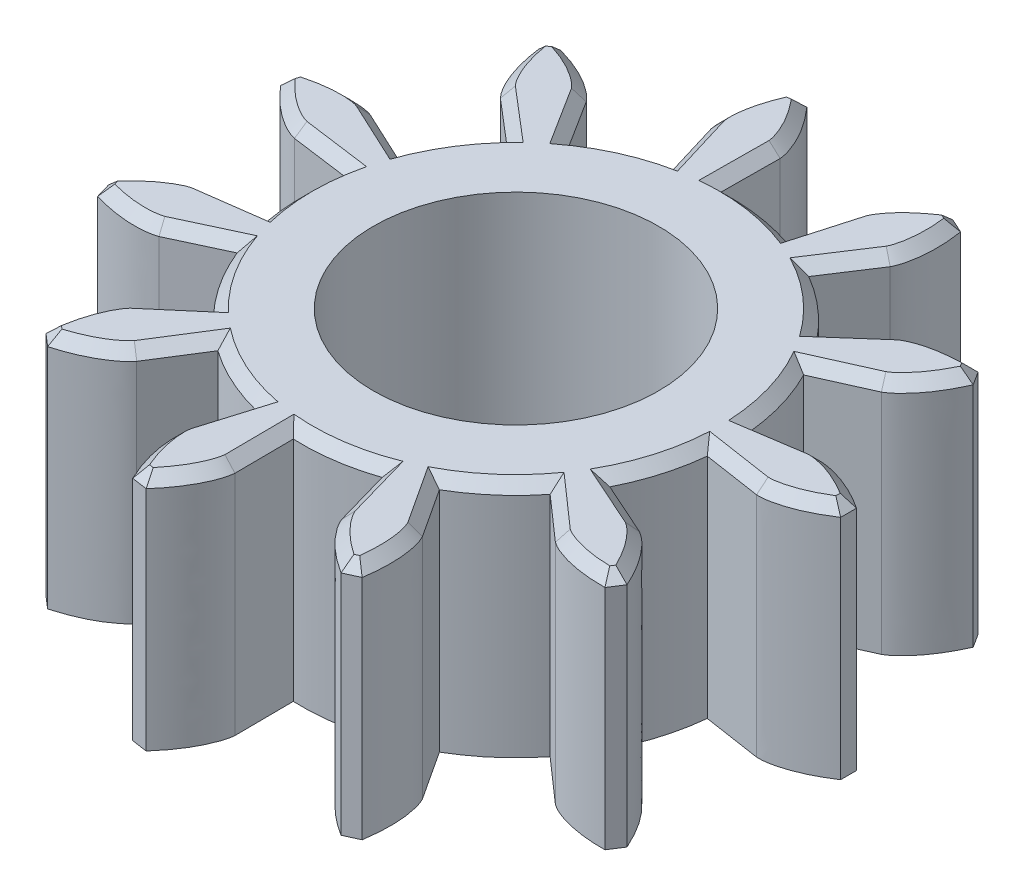
SolidWorks part; units mm, degrees
ref_plane "Front Plane" through (0, 0, 0) normal (0, 0, 1) x (1, 0, 0)
ref_plane "Top Plane" through (0, 0, 0) normal (0, 1, 0) x (1, 0, 0)
ref_plane "Right Plane" through (0, 0, 0) normal (1, 0, 0) x (0, 0, -1)
ref_plane "Plane1" through (0, -5, 0) normal (0, -1, 0) x (1, 0, 0)
sketch "Sketch1" plane through (0, -5, 0) normal (0, -1, 0) x (1, 0, 0)
  line L0 (3.1902, -2.808) -> (3.8796, -3.4147)
  line L1 (5.3253, -3.727) -> (5.6025, -3.2958)
  line L2 (4.7178, -2.1104) -> (3.8795, -1.7354)
  line L3 (4.2019, -0.6375) -> (5.1098, -0.7752)
  line L4 (6.4949, -0.2563) -> (6.4949, 0.2563)
  line L5 (5.1098, 0.7752) -> (4.2019, 0.6375)
  line L6 (3.8795, 1.7354) -> (4.7178, 2.1104)
  line L7 (5.6025, 3.2958) -> (5.3253, 3.727)
  line L8 (3.8796, 3.4147) -> (3.1902, 2.808)
  line L9 (2.3254, 3.5574) -> (2.8279, 4.326)
  line L10 (2.9312, 5.8015) -> (2.465, 6.0145)
  line L11 (1.4175, 4.9701) -> (1.1657, 4.087)
  line L12 (0.033, 4.2499) -> (0.0401, 5.1682)
  line L13 (-0.6706, 6.4653) -> (-1.178, 6.3924)
  line L14 (-1.4945, 4.9475) -> (-1.229, 4.0684)
  line L15 (-2.2699, 3.5931) -> (-2.7604, 4.3694)
  line L16 (-4.0596, 5.0764) -> (-4.447, 4.7407)
  line L17 (-3.9321, 3.3541) -> (-3.2334, 2.7581)
  line L18 (-3.8521, 1.7955) -> (-4.6844, 2.1834)
  line L19 (-6.1596, 2.0758) -> (-6.3041, 1.5839)
  line L20 (-5.1213, 0.6958) -> (-4.2113, 0.5722)
  line L21 (-4.2113, -0.5722) -> (-5.1213, -0.6958)
  line L22 (-6.3041, -1.5839) -> (-6.1596, -2.0758)
  line L23 (-4.6844, -2.1834) -> (-3.8521, -1.7955)
  line L24 (-3.2334, -2.7581) -> (-3.9321, -3.3541)
  line L25 (-4.447, -4.7407) -> (-4.0596, -5.0764)
  line L26 (-2.7604, -4.3694) -> (-2.2699, -3.5931)
  line L27 (-1.229, -4.0684) -> (-1.4945, -4.9475)
  line L28 (-1.178, -6.3924) -> (-0.6706, -6.4653)
  line L29 (0.0401, -5.1682) -> (0.033, -4.2499)
  line L30 (1.1657, -4.087) -> (1.4175, -4.9701)
  line L31 (2.465, -6.0145) -> (2.9312, -5.8015)
  line L32 (2.8279, -4.326) -> (2.3254, -3.5574)
  arc A0 (2.3254, -3.5574) -> (3.1902, -2.808) centre (0, 0) ccw
  arc A1 (3.8795, -1.7354) -> (4.2019, -0.6375) centre (0, 0) ccw
  arc A2 (4.2019, 0.6375) -> (3.8795, 1.7354) centre (0, 0) ccw
  arc A3 (3.1902, 2.808) -> (2.3254, 3.5574) centre (0, 0) ccw
  arc A4 (1.1657, 4.087) -> (0.033, 4.2499) centre (0, 0) ccw
  arc A5 (-1.229, 4.0684) -> (-2.2699, 3.5931) centre (0, 0) ccw
  arc A6 (-3.2334, 2.7581) -> (-3.8521, 1.7955) centre (0, 0) ccw
  arc A7 (-4.2113, 0.5722) -> (-4.2113, -0.5722) centre (0, 0) ccw
  arc A8 (-3.8521, -1.7955) -> (-3.2334, -2.7581) centre (0, 0) ccw
  arc A9 (-2.2699, -3.5931) -> (-1.229, -4.0684) centre (0, 0) ccw
  arc A10 (0.033, -4.2499) -> (1.1657, -4.087) centre (0, 0) ccw
  ellipse E0 centre (5.2837, -2.9889) end of major axis (6.9215, -2.923) minor radius 0.7393 (3.8796, -3.4147) -> (5.3253, -3.727) ccw
  ellipse E1 centre (4.9239, -3.5316) end of major axis (5.5451, -5.0133) minor radius 0.7173 (5.6025, -3.2958) -> (4.7178, -2.1104) ccw
  ellipse E2 centre (6.0609, 0.3422) end of major axis (7.403, 1.283) minor radius 0.7393 (5.1098, -0.7752) -> (6.4949, -0.2563) ccw
  ellipse E3 centre (6.0515, -0.3089) end of major axis (7.3752, -1.2195) minor radius 0.7173 (6.4949, 0.2563) -> (5.1098, 0.7752) ccw
  ellipse E4 centre (4.9137, 3.5646) end of major axis (4.2933, 2.0475) minor radius 0.7393 (4.7178, 2.1104) -> (5.6025, 3.2958) ccw
  ellipse E5 centre (5.2579, 3.0118) end of major axis (6.8637, 2.9614) minor radius 0.7173 (5.3253, 3.727) -> (3.8796, 3.4147) ccw
  ellipse E6 centre (2.2065, 5.6553) end of major axis (2.5048, 4.0436) minor radius 0.7393 (2.8279, 4.326) -> (2.9312, 5.8015) ccw
  ellipse E7 centre (2.7949, 5.3763) end of major axis (4.1731, 6.2021) minor radius 0.7173 (2.465, 6.0145) -> (1.4175, 4.9701) ccw
  ellipse E8 centre (-1.2013, 5.9505) end of major axis (-0.079, 4.7559) minor radius 0.7393 (0.0401, 5.1682) -> (-0.6706, 6.4653) ccw
  ellipse E9 centre (-0.5554, 6.0339) end of major axis (-1.2684, 4.5942) minor radius 0.7173 (-1.178, 6.3924) -> (-1.4945, 4.9475) ccw
  ellipse E10 centre (-4.2276, 4.3564) end of major axis (-2.6377, 3.9582) minor radius 0.7393 (-2.7604, 4.3694) -> (-4.0596, 5.0764) ccw
  ellipse E11 centre (-3.7295, 4.7758) end of major axis (-3.5509, 3.1791) minor radius 0.7173 (-4.447, 4.7407) -> (-3.9321, 3.3541) ccw
  ellipse E12 centre (-5.9118, 1.3792) end of major axis (-4.3589, 1.9038) minor radius 0.7393 (-4.6844, 2.1834) -> (-6.1596, 2.0758) ccw
  ellipse E13 centre (-5.7194, 2.0013) end of major axis (-4.7059, 0.7547) minor radius 0.7173 (-6.3041, 1.5839) -> (-5.1213, 0.6958) ccw
  ellipse E14 centre (-5.7189, -2.0359) end of major axis (-6.7417, -3.3167) minor radius 0.7393 (-5.1213, -0.6958) -> (-6.3041, -1.5839) ccw
  ellipse E15 centre (-5.8934, -1.4085) end of major axis (-4.3669, -1.9093) minor radius 0.7173 (-6.1596, -2.0758) -> (-4.6844, -2.1834) ccw
  ellipse E16 centre (-3.7104, -4.8046) end of major axis (-3.8783, -6.435) minor radius 0.7393 (-3.9321, -3.3541) -> (-4.447, -4.7407) ccw
  ellipse E17 centre (-4.1964, -4.3712) end of major axis (-2.6414, -3.9671) minor radius 0.7173 (-4.0596, -5.0764) -> (-2.7604, -4.3694) ccw
  ellipse E18 centre (-0.5238, -6.0479) end of major axis (0.2164, -7.5103) minor radius 0.7393 (-1.4945, -4.9475) -> (-1.178, -6.3924) ccw
  ellipse E19 centre (-1.167, -5.946) end of major axis (-2.2567, -7.1265) minor radius 0.7173 (-0.6706, -6.4653) -> (0.0401, -5.1682) ccw
  ellipse E20 centre (2.829, -5.371) end of major axis (4.2424, -6.2011) minor radius 0.7393 (1.4175, -4.9701) -> (2.465, -6.0145) ccw
  ellipse E21 centre (2.2329, -5.633) end of major axis (1.9544, -7.2153) minor radius 0.7173 (2.9312, -5.8015) -> (2.8279, -4.326) ccw
  point P4 (5.2837, -2.9889)
  point P5 (6.9215, -2.923)
  point P6 (5.3134, -3.7275)
  point P7 (3.8796, -3.4147)
  point P8 (5.3253, -3.727)
  point P9 (4.5558, -3.6748)
  point P10 (6.0117, -2.3029)
  point P18 (4.9239, -3.5316)
  point P19 (5.5853, -3.2543)
  point P20 (5.5451, -5.0133)
  point P21 (5.6025, -3.2958)
  point P22 (4.7178, -2.1104)
  point P23 (5.2353, -2.6175)
  point P24 (4.6124, -4.4457)
  point P34 (6.0609, 0.3422)
  point P35 (7.403, 1.283)
  point P36 (6.4852, -0.2632)
  point P37 (5.1098, -0.7752)
  point P38 (6.4949, -0.2563)
  point P39 (5.8193, -0.6284)
  point P40 (6.3024, 1.3128)
  point P48 (6.0515, -0.3089)
  point P49 (7.3752, -1.2195)
  point P50 (5.645, -0.8998)
  point P51 (6.4949, 0.2563)
  point P52 (5.1098, 0.7752)
  point P53 (5.8193, 0.6284)
  point P54 (6.2837, -1.2463)
  point P64 (4.9137, 3.5646)
  point P65 (5.598, 3.2848)
  point P66 (4.2933, 2.0475)
  point P67 (4.7178, 2.1104)
  point P68 (5.6025, 3.2958)
  point P69 (5.2353, 2.6175)
  point P70 (4.5921, 4.5117)
  point P78 (5.2579, 3.0118)
  point P79 (6.8637, 2.9614)
  point P80 (5.2354, 2.2949)
  point P81 (5.3253, 3.727)
  point P82 (3.8796, 3.4147)
  point P83 (4.5558, 3.6748)
  point P84 (5.96, 2.3488)
  point P94 (2.2065, 5.6553)
  point P95 (2.9334, 5.7898)
  point P96 (2.5048, 4.0436)
  point P97 (2.8279, 4.326)
  point P98 (2.9312, 5.8015)
  point P99 (2.9891, 5.0324)
  point P100 (1.4239, 6.2782)
  point P108 (2.7949, 5.3763)
  point P109 (4.1731, 6.2021)
  point P110 (3.1635, 4.7611)
  point P111 (2.465, 6.0145)
  point P112 (1.4175, 4.9701)
  point P113 (1.8458, 5.5545)
  point P114 (3.744, 5.1982)
  point P124 (-1.2013, 5.9505)
  point P125 (-0.6625, 6.4566)
  point P126 (-0.079, 4.7559)
  point P127 (0.0401, 5.1682)
  point P128 (-0.6706, 6.4653)
  point P129 (-0.2061, 5.8496)
  point P130 (-2.1964, 6.0514)
  point P138 (-0.5554, 6.0339)
  point P139 (0.0873, 5.7156)
  point P140 (-1.2684, 4.5942)
  point P141 (-1.178, 6.3924)
  point P142 (-1.4945, 4.9475)
  point P143 (-1.4502, 5.6707)
  point P144 (0.3393, 6.3971)
  point P154 (-4.2276, 4.3564)
  point P155 (-2.6377, 3.9582)
  point P156 (-4.4072, 3.6393)
  point P157 (-2.7604, 4.3694)
  point P158 (-4.0596, 5.0764)
  point P159 (-3.3359, 4.8095)
  point P160 (-5.1193, 3.9033)
  point P168 (-3.7295, 4.7758)
  point P169 (-3.0166, 4.8555)
  point P170 (-3.5509, 3.1791)
  point P171 (-4.447, 4.7407)
  point P172 (-3.9321, 3.3541)
  point P173 (-4.2858, 3.9864)
  point P174 (-3.1731, 5.5651)
  point P184 (-5.9118, 1.3792)
  point P185 (-4.3589, 1.9038)
  point P186 (-5.6752, 0.6788)
  point P187 (-4.6844, 2.1834)
  point P188 (-6.1596, 2.0758)
  point P189 (-5.4066, 2.2425)
  point P190 (-6.4169, 0.5159)
  point P198 (-5.7194, 2.0013)
  point P199 (-5.1628, 2.4538)
  point P200 (-4.7059, 0.7547)
  point P201 (-6.3041, 1.5839)
  point P202 (-5.1213, 0.6958)
  point P203 (-5.7607, 1.0365)
  point P204 (-5.6781, 2.9661)
  point P214 (-5.7189, -2.0359)
  point P215 (-5.1413, -2.4972)
  point P216 (-6.7417, -3.3167)
  point P217 (-5.1213, -0.6958)
  point P218 (-6.3041, -1.5839)
  point P219 (-5.7607, -1.0365)
  point P220 (-5.6772, -3.0352)
  point P228 (-5.8934, -1.4085)
  point P229 (-4.3669, -1.9093)
  point P230 (-6.117, -2.09)
  point P231 (-6.1596, -2.0758)
  point P232 (-4.6844, -2.1834)
  point P233 (-5.4066, -2.2425)
  point P234 (-6.3803, -0.5745)
  point P244 (-3.7104, -4.8046)
  point P245 (-2.975, -4.8803)
  point P246 (-3.8783, -6.435)
  point P247 (-3.9321, -3.3541)
  point P248 (-4.447, -4.7407)
  point P249 (-4.2858, -3.9864)
  point P250 (-3.135, -5.6227)
  point P258 (-4.1964, -4.3712)
  point P259 (-2.6414, -3.9671)
  point P260 (-4.016, -5.0654)
  point P261 (-4.0596, -5.0764)
  point P262 (-2.7604, -4.3694)
  point P263 (-3.3359, -4.8095)
  point P264 (-5.0568, -3.9328)
  point P274 (-0.5238, -6.0479)
  point P275 (0.1357, -5.714)
  point P276 (0.2164, -7.5103)
  point P277 (-1.4945, -4.9475)
  point P278 (-1.178, -6.3924)
  point P279 (-1.4502, -5.6707)
  point P280 (0.4025, -6.4251)
  point P288 (-1.167, -5.946)
  point P289 (-0.6399, -6.4325)
  point P290 (-2.2567, -7.1265)
  point P291 (-0.6706, -6.4653)
  point P292 (0.0401, -5.1682)
  point P293 (-0.2061, -5.8496)
  point P294 (-2.1279, -6.0424)
  point P304 (2.829, -5.371)
  point P305 (4.2424, -6.2011)
  point P306 (2.4547, -6.0085)
  point P307 (1.4175, -4.9701)
  point P308 (2.465, -6.0145)
  point P309 (1.8458, -5.5545)
  point P310 (3.8123, -5.1875)
  point P318 (2.2329, -5.633)
  point P319 (2.9393, -5.7573)
  point P320 (1.9544, -7.2153)
  point P321 (2.9312, -5.8015)
  point P322 (2.8279, -4.326)
  point P323 (2.9891, -5.0324)
  point P324 (1.4767, -6.2336)
extrude "Boss-Extrude1" add sketch "Sketch1" against normal blind 4.5
sketch "Sketch2" plane through (0, -0.5, 0) normal (0, 1, 0) x (1, 0, 0)
  line L0 (-0.1686, 4.0465) -> (-0.1599, 5.1595)
  line L1 (-0.7466, 6.2523) -> (-1.0451, 6.2094)
  line L2 (-1.3001, 4.9954) -> (-0.9783, 3.9301)
  line L3 (-2.3295, 3.313) -> (-2.924, 4.2539)
  line L4 (-4.0083, 4.8562) -> (-4.2363, 4.6587)
  line L5 (-3.7944, 3.4995) -> (-2.9477, 2.7773)
  line L6 (-3.7508, 1.5276) -> (-4.7597, 1.9978)
  line L7 (-5.9975, 1.9182) -> (-6.0824, 1.6288)
  line L8 (-5.084, 0.8926) -> (-3.9813, 0.7427)
  line L9 (-3.9813, -0.7427) -> (-5.0842, -0.8926)
  line L10 (-6.0825, -1.6288) -> (-5.9975, -1.9182)
  line L11 (-4.7595, -1.9978) -> (-3.7508, -1.5276)
  line L12 (-2.9477, -2.7773) -> (-3.7945, -3.4996)
  line L13 (-4.2363, -4.6586) -> (-4.0083, -4.8562)
  line L14 (-2.9239, -4.2538) -> (-2.3295, -3.313)
  line L15 (-0.9783, -3.9301) -> (-1.3001, -4.9955)
  line L16 (-1.0452, -6.2094) -> (-0.7466, -6.2523)
  line L17 (-0.1599, -5.1593) -> (-0.1686, -4.0465)
  line L18 (1.3018, -3.8351) -> (1.6071, -4.9054)
  line L19 (2.4778, -5.7887) -> (2.7522, -5.6634)
  line L20 (2.6548, -4.4268) -> (2.0459, -3.4953)
  line L21 (3.1685, -2.5225) -> (4.004, -3.2579)
  line L22 (5.2141, -3.5302) -> (5.3772, -3.2764)
  line L23 (4.6266, -2.2888) -> (3.6108, -1.8343)
  line L24 (4.0293, -0.409) -> (5.1297, -0.576)
  line L25 (6.2949, -0.1508) -> (6.2949, 0.1508)
  line L26 (5.1296, 0.5759) -> (4.0293, 0.409)
  line L27 (3.6108, 1.8343) -> (4.6268, 2.2888)
  line L28 (5.3772, 3.2764) -> (5.2141, 3.5302)
  line L29 (4.0039, 3.2578) -> (3.1685, 2.5225)
  line L30 (2.0459, 3.4953) -> (2.6549, 4.4269)
  line L31 (2.7522, 5.6634) -> (2.4778, 5.7887)
  line L32 (1.607, 4.9053) -> (1.3018, 3.8351)
  line L33 (2.3254, 3.5574) -> (2.8279, 4.326)
  line L34 (2.9312, 5.8015) -> (2.465, 6.0145)
  line L35 (1.4175, 4.9701) -> (1.1657, 4.087)
  line L36 (0.033, 4.2499) -> (0.0401, 5.1682)
  line L37 (-0.6706, 6.4653) -> (-1.178, 6.3924)
  line L38 (-1.4945, 4.9475) -> (-1.229, 4.0684)
  line L39 (-2.2699, 3.5931) -> (-2.7604, 4.3694)
  line L40 (-4.0596, 5.0764) -> (-4.447, 4.7407)
  line L41 (-3.9321, 3.3541) -> (-3.2334, 2.7581)
  line L42 (-3.8521, 1.7955) -> (-4.6844, 2.1834)
  line L43 (-6.1596, 2.0758) -> (-6.3041, 1.5839)
  line L44 (-5.1213, 0.6958) -> (-4.2113, 0.5722)
  line L45 (-4.2113, -0.5722) -> (-5.1213, -0.6958)
  line L46 (-6.3041, -1.5839) -> (-6.1596, -2.0758)
  line L47 (-4.6844, -2.1834) -> (-3.8521, -1.7955)
  line L48 (-3.2334, -2.7581) -> (-3.9321, -3.3541)
  line L49 (-4.447, -4.7407) -> (-4.0596, -5.0764)
  line L50 (-2.7604, -4.3694) -> (-2.2699, -3.5931)
  line L51 (-1.229, -4.0684) -> (-1.4945, -4.9475)
  line L52 (-1.178, -6.3924) -> (-0.6706, -6.4653)
  line L53 (0.0401, -5.1682) -> (0.033, -4.2499)
  line L54 (1.1657, -4.087) -> (1.4175, -4.9701)
  line L55 (2.465, -6.0145) -> (2.9312, -5.8015)
  line L56 (2.8279, -4.326) -> (2.3254, -3.5574)
  line L57 (3.1902, -2.808) -> (3.8796, -3.4147)
  line L58 (5.3253, -3.727) -> (5.6025, -3.2958)
  line L59 (4.7178, -2.1104) -> (3.8795, -1.7354)
  line L60 (4.2019, -0.6375) -> (5.1098, -0.7752)
  line L61 (6.4949, -0.2563) -> (6.4949, 0.2563)
  line L62 (5.1098, 0.7752) -> (4.2019, 0.6375)
  line L63 (3.8795, 1.7354) -> (4.7178, 2.1104)
  line L64 (5.6025, 3.2958) -> (5.3253, 3.727)
  line L65 (3.8796, 3.4147) -> (3.1902, 2.808)
  line L66 (2.3254, 3.5574) -> (2.8279, 4.326)
  line L67 (2.9312, 5.8015) -> (2.465, 6.0145)
  line L68 (1.4175, 4.9701) -> (1.1657, 4.087)
  line L69 (0.033, 4.2499) -> (0.0401, 5.1682)
  line L70 (-0.6706, 6.4653) -> (-1.178, 6.3924)
  line L71 (-1.4945, 4.9475) -> (-1.229, 4.0684)
  line L72 (-2.2699, 3.5931) -> (-2.7604, 4.3694)
  line L73 (-4.0596, 5.0764) -> (-4.447, 4.7407)
  line L74 (-3.9321, 3.3541) -> (-3.2334, 2.7581)
  line L75 (-3.8521, 1.7955) -> (-4.6844, 2.1834)
  line L76 (-6.1596, 2.0758) -> (-6.3041, 1.5839)
  line L77 (-5.1213, 0.6958) -> (-4.2113, 0.5722)
  line L78 (-4.2113, -0.5722) -> (-5.1213, -0.6958)
  line L79 (-6.3041, -1.5839) -> (-6.1596, -2.0758)
  line L80 (-4.6844, -2.1834) -> (-3.8521, -1.7955)
  line L81 (-3.2334, -2.7581) -> (-3.9321, -3.3541)
  line L82 (-4.447, -4.7407) -> (-4.0596, -5.0764)
  line L83 (-2.7604, -4.3694) -> (-2.2699, -3.5931)
  line L84 (-1.229, -4.0684) -> (-1.4945, -4.9475)
  line L85 (-1.178, -6.3924) -> (-0.6706, -6.4653)
  line L86 (0.0401, -5.1682) -> (0.033, -4.2499)
  line L87 (1.1657, -4.087) -> (1.4175, -4.9701)
  line L88 (2.465, -6.0145) -> (2.9312, -5.8015)
  line L89 (2.8279, -4.326) -> (2.3254, -3.5574)
  line L90 (3.1902, -2.808) -> (3.8796, -3.4147)
  line L91 (5.3253, -3.727) -> (5.6025, -3.2958)
  line L92 (4.7178, -2.1104) -> (3.8795, -1.7354)
  line L93 (4.2019, -0.6375) -> (5.1098, -0.7752)
  line L94 (6.4949, -0.2563) -> (6.4949, 0.2563)
  line L95 (5.1098, 0.7752) -> (4.2019, 0.6375)
  line L96 (3.8795, 1.7354) -> (4.7178, 2.1104)
  line L97 (5.6025, 3.2958) -> (5.3253, 3.727)
  line L98 (3.8796, 3.4147) -> (3.1902, 2.808)
  arc A0 (-0.9783, 3.9301) -> (-2.3295, 3.313) centre (0, 0) ccw
  arc A1 (-2.9477, 2.7773) -> (-3.7508, 1.5276) centre (0, 0) ccw
  arc A2 (-3.9813, 0.7427) -> (-3.9813, -0.7427) centre (0, 0) ccw
  arc A3 (-3.7508, -1.5276) -> (-2.9477, -2.7773) centre (0, 0) ccw
  arc A4 (-2.3295, -3.313) -> (-0.9783, -3.9301) centre (0, 0) ccw
  arc A5 (-0.1686, -4.0465) -> (1.3018, -3.8351) centre (0, 0) ccw
  arc A6 (2.0459, -3.4953) -> (3.1685, -2.5225) centre (0, 0) ccw
  arc A7 (3.6108, -1.8343) -> (4.0293, -0.409) centre (0, 0) ccw
  arc A8 (4.0293, 0.409) -> (3.6108, 1.8343) centre (0, 0) ccw
  arc A9 (3.1685, 2.5225) -> (2.0459, 3.4953) centre (0, 0) ccw
  arc A10 (1.3018, 3.8351) -> (-0.1686, 4.0465) centre (0, 0) ccw
  arc A11 (3.1902, 2.808) -> (2.3254, 3.5574) centre (0, 0) ccw
  arc A12 (1.1657, 4.087) -> (0.033, 4.2499) centre (0, 0) ccw
  arc A13 (-1.229, 4.0684) -> (-2.2699, 3.5931) centre (0, 0) ccw
  arc A14 (-3.2334, 2.7581) -> (-3.8521, 1.7955) centre (0, 0) ccw
  arc A15 (-4.2113, 0.5722) -> (-4.2113, -0.5722) centre (0, 0) ccw
  arc A16 (-3.8521, -1.7955) -> (-3.2334, -2.7581) centre (0, 0) ccw
  arc A17 (-2.2699, -3.5931) -> (-1.229, -4.0684) centre (0, 0) ccw
  arc A18 (0.033, -4.2499) -> (1.1657, -4.087) centre (0, 0) ccw
  arc A19 (2.3254, -3.5574) -> (3.1902, -2.808) centre (0, 0) ccw
  arc A20 (3.8795, -1.7354) -> (4.2019, -0.6375) centre (0, 0) ccw
  arc A21 (4.2019, 0.6375) -> (3.8795, 1.7354) centre (0, 0) ccw
  arc A22 (3.1902, 2.808) -> (2.3254, 3.5574) centre (0, 0) ccw
  arc A23 (1.1657, 4.087) -> (0.033, 4.2499) centre (0, 0) ccw
  arc A24 (-1.229, 4.0684) -> (-2.2699, 3.5931) centre (0, 0) ccw
  arc A25 (-3.2334, 2.7581) -> (-3.8521, 1.7955) centre (0, 0) ccw
  arc A26 (-4.2113, 0.5722) -> (-4.2113, -0.5722) centre (0, 0) ccw
  arc A27 (-3.8521, -1.7955) -> (-3.2334, -2.7581) centre (0, 0) ccw
  arc A28 (-2.2699, -3.5931) -> (-1.229, -4.0684) centre (0, 0) ccw
  arc A29 (0.033, -4.2499) -> (1.1657, -4.087) centre (0, 0) ccw
  arc A30 (2.3254, -3.5574) -> (3.1902, -2.808) centre (0, 0) ccw
  arc A31 (3.8795, -1.7354) -> (4.2019, -0.6375) centre (0, 0) ccw
  arc A32 (4.2019, 0.6375) -> (3.8795, 1.7354) centre (0, 0) ccw
  circle A33 centre (0, 0) radius 2.7
  ellipse E22 centre (2.2329, 5.633) end of major axis (1.9544, 7.2153) minor radius 0.7173 (2.8279, 4.326) -> (2.9312, 5.8015) ccw
  ellipse E23 centre (2.829, 5.371) end of major axis (4.2424, 6.2011) minor radius 0.7393 (2.465, 6.0145) -> (1.4175, 4.9701) ccw
  ellipse E24 centre (-1.167, 5.946) end of major axis (-2.2567, 7.1265) minor radius 0.7173 (0.0401, 5.1682) -> (-0.6706, 6.4653) ccw
  ellipse E25 centre (-0.5238, 6.0479) end of major axis (0.2164, 7.5103) minor radius 0.7393 (-1.178, 6.3924) -> (-1.4945, 4.9475) ccw
  ellipse E26 centre (-4.1964, 4.3712) end of major axis (-2.6414, 3.9671) minor radius 0.7173 (-2.7604, 4.3694) -> (-4.0596, 5.0764) ccw
  ellipse E27 centre (-3.7104, 4.8046) end of major axis (-3.8783, 6.435) minor radius 0.7393 (-4.447, 4.7407) -> (-3.9321, 3.3541) ccw
  ellipse E28 centre (-5.8934, 1.4085) end of major axis (-4.3669, 1.9093) minor radius 0.7173 (-4.6844, 2.1834) -> (-6.1596, 2.0758) ccw
  ellipse E29 centre (-5.7189, 2.0359) end of major axis (-6.7417, 3.3167) minor radius 0.7393 (-6.3041, 1.5839) -> (-5.1213, 0.6958) ccw
  ellipse E30 centre (-5.7194, -2.0013) end of major axis (-4.7059, -0.7547) minor radius 0.7173 (-5.1213, -0.6958) -> (-6.3041, -1.5839) ccw
  ellipse E31 centre (-5.9118, -1.3792) end of major axis (-4.3589, -1.9038) minor radius 0.7393 (-6.1596, -2.0758) -> (-4.6844, -2.1834) ccw
  ellipse E32 centre (-3.7295, -4.7758) end of major axis (-3.5509, -3.1791) minor radius 0.7173 (-3.9321, -3.3541) -> (-4.447, -4.7407) ccw
  ellipse E33 centre (-4.2276, -4.3564) end of major axis (-2.6377, -3.9582) minor radius 0.7393 (-4.0596, -5.0764) -> (-2.7604, -4.3694) ccw
  ellipse E34 centre (-0.5554, -6.0339) end of major axis (-1.2684, -4.5942) minor radius 0.7173 (-1.4945, -4.9475) -> (-1.178, -6.3924) ccw
  ellipse E35 centre (-1.2013, -5.9505) end of major axis (-0.079, -4.7559) minor radius 0.7393 (-0.6706, -6.4653) -> (0.0401, -5.1682) ccw
  ellipse E36 centre (2.7949, -5.3763) end of major axis (4.1731, -6.2021) minor radius 0.7173 (1.4175, -4.9701) -> (2.465, -6.0145) ccw
  ellipse E37 centre (2.2065, -5.6553) end of major axis (2.5048, -4.0436) minor radius 0.7393 (2.9312, -5.8015) -> (2.8279, -4.326) ccw
  ellipse E38 centre (5.2579, -3.0118) end of major axis (3.6521, -3.0623) minor radius 0.7173 (3.8796, -3.4147) -> (5.3253, -3.727) ccw
  ellipse E39 centre (4.9137, -3.5646) end of major axis (4.2933, -2.0475) minor radius 0.7393 (5.6025, -3.2958) -> (4.7178, -2.1104) ccw
  ellipse E40 centre (6.0515, 0.3089) end of major axis (4.7279, -0.6017) minor radius 0.7173 (5.1098, -0.7752) -> (6.4949, -0.2563) ccw
  ellipse E41 centre (6.0609, -0.3422) end of major axis (7.403, -1.283) minor radius 0.7393 (6.4949, 0.2563) -> (5.1098, 0.7752) ccw
  ellipse E42 centre (4.9239, 3.5316) end of major axis (5.5451, 5.0133) minor radius 0.7173 (4.7178, 2.1104) -> (5.6025, 3.2958) ccw
  ellipse E43 centre (5.2837, 2.9889) end of major axis (3.646, 3.0547) minor radius 0.7393 (5.3253, 3.727) -> (3.8796, 3.4147) ccw
  ellipse E44 centre (2.2329, 5.633) end of major axis (1.9544, 7.2153) minor radius 0.7173 (2.8279, 4.326) -> (2.9312, 5.8015) ccw
  ellipse E45 centre (2.829, 5.371) end of major axis (4.2424, 6.2011) minor radius 0.7393 (2.465, 6.0145) -> (1.4175, 4.9701) ccw
  ellipse E46 centre (-1.167, 5.946) end of major axis (-2.2567, 7.1265) minor radius 0.7173 (0.0401, 5.1682) -> (-0.6706, 6.4653) ccw
  ellipse E47 centre (-0.5238, 6.0479) end of major axis (0.2164, 7.5103) minor radius 0.7393 (-1.178, 6.3924) -> (-1.4945, 4.9475) ccw
  ellipse E48 centre (-4.1964, 4.3712) end of major axis (-2.6414, 3.9671) minor radius 0.7173 (-2.7604, 4.3694) -> (-4.0596, 5.0764) ccw
  ellipse E49 centre (-3.7104, 4.8046) end of major axis (-3.8783, 6.435) minor radius 0.7393 (-4.447, 4.7407) -> (-3.9321, 3.3541) ccw
  ellipse E50 centre (-5.8934, 1.4085) end of major axis (-4.3669, 1.9093) minor radius 0.7173 (-4.6844, 2.1834) -> (-6.1596, 2.0758) ccw
  ellipse E51 centre (-5.7189, 2.0359) end of major axis (-6.7417, 3.3167) minor radius 0.7393 (-6.3041, 1.5839) -> (-5.1213, 0.6958) ccw
  ellipse E52 centre (-5.7194, -2.0013) end of major axis (-4.7059, -0.7547) minor radius 0.7173 (-5.1213, -0.6958) -> (-6.3041, -1.5839) ccw
  ellipse E53 centre (-5.9118, -1.3792) end of major axis (-4.3589, -1.9038) minor radius 0.7393 (-6.1596, -2.0758) -> (-4.6844, -2.1834) ccw
  ellipse E54 centre (-3.7295, -4.7758) end of major axis (-3.5509, -3.1791) minor radius 0.7173 (-3.9321, -3.3541) -> (-4.447, -4.7407) ccw
  ellipse E55 centre (-4.2276, -4.3564) end of major axis (-2.6377, -3.9582) minor radius 0.7393 (-4.0596, -5.0764) -> (-2.7604, -4.3694) ccw
  ellipse E56 centre (-0.5554, -6.0339) end of major axis (-1.2684, -4.5942) minor radius 0.7173 (-1.4945, -4.9475) -> (-1.178, -6.3924) ccw
  ellipse E57 centre (-1.2013, -5.9505) end of major axis (-0.079, -4.7559) minor radius 0.7393 (-0.6706, -6.4653) -> (0.0401, -5.1682) ccw
  ellipse E58 centre (2.7949, -5.3763) end of major axis (4.1731, -6.2021) minor radius 0.7173 (1.4175, -4.9701) -> (2.465, -6.0145) ccw
  ellipse E59 centre (2.2065, -5.6553) end of major axis (2.5048, -4.0436) minor radius 0.7393 (2.9312, -5.8015) -> (2.8279, -4.326) ccw
  ellipse E60 centre (5.2579, -3.0118) end of major axis (6.8637, -2.9614) minor radius 0.7173 (3.8796, -3.4147) -> (5.3253, -3.727) ccw
  ellipse E61 centre (4.9137, -3.5646) end of major axis (4.2933, -2.0475) minor radius 0.7393 (5.6025, -3.2958) -> (4.7178, -2.1104) ccw
  ellipse E62 centre (6.0515, 0.3089) end of major axis (7.3752, 1.2195) minor radius 0.7173 (5.1098, -0.7752) -> (6.4949, -0.2563) ccw
  ellipse E63 centre (6.0609, -0.3422) end of major axis (7.403, -1.283) minor radius 0.7393 (6.4949, 0.2563) -> (5.1098, 0.7752) ccw
  ellipse E64 centre (4.9239, 3.5316) end of major axis (5.5451, 5.0133) minor radius 0.7173 (4.7178, 2.1104) -> (5.6025, 3.2958) ccw
  ellipse E65 centre (5.2837, 2.9889) end of major axis (6.9215, 2.923) minor radius 0.7393 (5.3253, 3.727) -> (3.8796, 3.4147) ccw
  spline S0 degree 1 poles (-0.1599, 5.1595) (-0.7466, 6.2523) knots 0 0 1 1 construction
  spline S1 degree 1 poles (-1.0451, 6.2094) (-1.3001, 4.9954) knots 0 0 1 1 construction
  spline S2 degree 1 poles (-2.924, 4.2539) (-4.0083, 4.8562) knots 0 0 1 1 construction
  spline S3 degree 1 poles (-4.2363, 4.6587) (-3.7944, 3.4995) knots 0 0 1 1 construction
  spline S4 degree 1 poles (-4.7597, 1.9978) (-5.9975, 1.9182) knots 0 0 1 1 construction
  spline S5 degree 1 poles (-6.0824, 1.6288) (-5.084, 0.8926) knots 0 0 1 1 construction
  spline S6 degree 1 poles (-5.0842, -0.8926) (-6.0825, -1.6288) knots 0 0 1 1 construction
  spline S7 degree 1 poles (-5.9975, -1.9182) (-4.7595, -1.9978) knots 0 0 1 1 construction
  spline S8 degree 1 poles (-3.7945, -3.4996) (-4.2363, -4.6586) knots 0 0 1 1 construction
  spline S9 degree 1 poles (-4.0083, -4.8562) (-2.9239, -4.2538) knots 0 0 1 1 construction
  spline S10 degree 1 poles (-1.3001, -4.9955) (-1.0452, -6.2094) knots 0 0 1 1 construction
  spline S11 degree 1 poles (-0.7466, -6.2523) (-0.1599, -5.1593) knots 0 0 1 1 construction
  spline S12 degree 1 poles (1.6071, -4.9054) (2.4778, -5.7887) knots 0 0 1 1 construction
  spline S13 degree 1 poles (2.7522, -5.6634) (2.6548, -4.4268) knots 0 0 1 1 construction
  spline S14 degree 1 poles (4.004, -3.2579) (5.2141, -3.5302) knots 0 0 1 1 construction
  spline S15 degree 1 poles (5.3772, -3.2764) (4.6266, -2.2888) knots 0 0 1 1 construction
  spline S16 degree 1 poles (5.1297, -0.576) (6.2949, -0.1508) knots 0 0 1 1 construction
  spline S17 degree 1 poles (6.2949, 0.1508) (5.1296, 0.5759) knots 0 0 1 1 construction
  spline S18 degree 1 poles (4.6268, 2.2888) (5.3772, 3.2764) knots 0 0 1 1 construction
  spline S19 degree 1 poles (5.2141, 3.5302) (4.0039, 3.2578) knots 0 0 1 1 construction
  spline S20 degree 1 poles (2.6549, 4.4269) (2.7522, 5.6634) knots 0 0 1 1 construction
  spline S21 degree 1 poles (2.4778, 5.7887) (1.607, 4.9053) knots 0 0 1 1 construction
  spline S22 degree 3 poles (-0.1599, 5.1595) (-0.1679, 5.2382) (-0.201, 5.3778) (-0.3234, 5.6652) (-0.5064, 5.9612) (-0.6642, 6.1599) (-0.7466, 6.2523) knots -2.605383 -2.605383 -2.605383 -2.605383 -2.356634 -2.107886 -1.859137 -1.610389 -1.610389 -1.610389 -1.610389
  spline S23 degree 3 poles (-1.0451, 6.2094) (-1.0981, 6.0974) (-1.1937, 5.862) (-1.2857, 5.5272) (-1.3222, 5.2176) (-1.3145, 5.0735) (-1.3001, 4.9954) knots 1.629777 1.629777 1.629777 1.629777 1.874231 2.118685 2.363139 2.607593 2.607593 2.607593 2.607593
  spline S24 degree 3 poles (-2.924, 4.2539) (-2.9732, 4.3158) (-3.0765, 4.4154) (-3.3349, 4.591) (-3.6488, 4.7411) (-3.889, 4.8229) (-4.0083, 4.8562) knots 0.53621 0.53621 0.53621 0.53621 0.784958 1.033707 1.282455 1.531204 1.531204 1.531204 1.531204
  spline S25 degree 3 poles (-4.2363, 4.6587) (-4.2203, 4.5358) (-4.1734, 4.286) (-4.0698, 3.9547) (-3.9331, 3.6745) (-3.8488, 3.5574) (-3.7944, 3.4995) knots 1.629777 1.629777 1.629777 1.629777 1.874231 2.118685 2.363139 2.607593 2.607593 2.607593 2.607593
  spline S26 degree 3 poles (-4.7597, 1.9978) (-4.8346, 2.0233) (-4.9753, 2.0512) (-5.2876, 2.0592) (-5.6328, 2.0157) (-5.8791, 1.9547) (-5.9975, 1.9182) knots 0.53621 0.53621 0.53621 0.53621 0.784958 1.033707 1.282455 1.531204 1.531204 1.531204 1.531204
  spline S27 degree 3 poles (-6.0824, 1.6288) (-6.0026, 1.5341) (-5.8281, 1.3493) (-5.5618, 1.1266) (-5.2953, 0.9647) (-5.1611, 0.9119) (-5.084, 0.8926) knots 1.629777 1.629777 1.629777 1.629777 1.874231 2.118685 2.363139 2.607593 2.607593 2.607593 2.607593
  spline S28 degree 3 poles (-5.0842, -0.8926) (-5.161, -0.9117) (-5.2945, -0.9643) (-5.5615, -1.1264) (-5.8284, -1.3496) (-6.0026, -1.5341) (-6.0825, -1.6288) knots 0.53621 0.53621 0.53621 0.53621 0.784958 1.033707 1.282455 1.531204 1.531204 1.531204 1.531204
  spline S29 degree 3 poles (-5.9975, -1.9182) (-5.8791, -1.9547) (-5.6324, -2.0158) (-5.288, -2.0592) (-4.9763, -2.0513) (-4.8347, -2.0232) (-4.7595, -1.9978) knots -1.511816 -1.511816 -1.511816 -1.511816 -1.267362 -1.022908 -0.778454 -0.534 -0.534 -0.534 -0.534
  spline S30 degree 3 poles (-3.7945, -3.4996) (-3.8488, -3.5572) (-3.9327, -3.6736) (-4.0697, -3.9543) (-4.1735, -4.2864) (-4.2204, -4.5358) (-4.2363, -4.6586) knots 0.53621 0.53621 0.53621 0.53621 0.784958 1.033707 1.282455 1.531204 1.531204 1.531204 1.531204
  spline S31 degree 3 poles (-4.0083, -4.8562) (-3.889, -4.8229) (-3.6485, -4.7409) (-3.3352, -4.5912) (-3.0773, -4.416) (-2.9734, -4.3159) (-2.9239, -4.2538) knots -1.511816 -1.511816 -1.511816 -1.511816 -1.267362 -1.022908 -0.778454 -0.534 -0.534 -0.534 -0.534
  spline S32 degree 3 poles (-1.3001, -4.9955) (-1.3146, -5.0733) (-1.3223, -5.2166) (-1.2858, -5.5268) (-1.1936, -5.8623) (-1.0982, -6.0975) (-1.0452, -6.2094) knots 0.53621 0.53621 0.53621 0.53621 0.784958 1.033707 1.282455 1.531204 1.531204 1.531204 1.531204
  spline S33 degree 3 poles (-0.7466, -6.2523) (-0.6642, -6.1598) (-0.5061, -5.9608) (-0.3236, -5.6655) (-0.2013, -5.3787) (-0.1681, -5.2383) (-0.1599, -5.1593) knots -1.511816 -1.511816 -1.511816 -1.511816 -1.267362 -1.022908 -0.778454 -0.534 -0.534 -0.534 -0.534
  spline S34 degree 3 poles (1.6071, -4.9054) (1.6369, -4.9787) (1.7079, -5.1033) (1.9064, -5.3446) (2.1653, -5.577) (2.3727, -5.7232) (2.4778, -5.7887) knots -2.605383 -2.605383 -2.605383 -2.605383 -2.356634 -2.107886 -1.859137 -1.610389 -1.610389 -1.610389 -1.610389
  spline S35 degree 3 poles (2.7522, -5.6634) (2.7715, -5.541) (2.7969, -5.2882) (2.7908, -4.9411) (2.7386, -4.6337) (2.6906, -4.4976) (2.6548, -4.4268) knots -1.511816 -1.511816 -1.511816 -1.511816 -1.267362 -1.022908 -0.778454 -0.534 -0.534 -0.534 -0.534
  spline S36 degree 3 poles (4.004, -3.2579) (4.0687, -3.3034) (4.1959, -3.3698) (4.4933, -3.4655) (4.8367, -3.521) (5.0903, -3.5319) (5.2141, -3.5302) knots -2.605383 -2.605383 -2.605383 -2.605383 -2.356634 -2.107886 -1.859137 -1.610389 -1.610389 -1.610389 -1.610389
  spline S37 degree 3 poles (5.3772, -3.2764) (5.3272, -3.163) (5.2119, -2.9366) (5.0191, -2.6479) (4.809, -2.4175) (4.6951, -2.329) (4.6266, -2.2888) knots -1.511816 -1.511816 -1.511816 -1.511816 -1.267362 -1.022908 -0.778454 -0.534 -0.534 -0.534 -0.534
  spline S38 degree 3 poles (5.1297, -0.576) (5.2088, -0.5792) (5.3517, -0.5664) (5.6536, -0.4861) (5.9725, -0.3471) (6.1917, -0.2192) (6.2949, -0.1508) knots -2.605383 -2.605383 -2.605383 -2.605383 -2.356634 -2.107886 -1.859137 -1.610389 -1.610389 -1.610389 -1.610389
  spline S39 degree 3 poles (6.2949, 0.1508) (6.1916, 0.2192) (5.9722, 0.3473) (5.6539, 0.486) (5.3526, 0.5662) (5.2089, 0.5791) (5.1296, 0.5759) knots 1.629777 1.629777 1.629777 1.629777 1.874231 2.118685 2.363139 2.607593 2.607593 2.607593 2.607593
  spline S40 degree 3 poles (4.6268, 2.2888) (4.6951, 2.3288) (4.8083, 2.4168) (5.0189, 2.6476) (5.2121, 2.937) (5.3273, 3.1631) (5.3772, 3.2764) knots -2.605383 -2.605383 -2.605383 -2.605383 -2.356634 -2.107886 -1.859137 -1.610389 -1.610389 -1.610389 -1.610389
  spline S41 degree 3 poles (5.2141, 3.5302) (5.0902, 3.5318) (4.8363, 3.521) (4.4936, 3.4656) (4.1968, 3.3702) (4.0689, 3.3033) (4.0039, 3.2578) knots 1.629777 1.629777 1.629777 1.629777 1.874231 2.118685 2.363139 2.607593 2.607593 2.607593 2.607593
  spline S42 degree 3 poles (2.6549, 4.4269) (2.6907, 4.4974) (2.7384, 4.6327) (2.7908, 4.9407) (2.7969, 5.2886) (2.7715, 5.5411) (2.7522, 5.6634) knots -2.605383 -2.605383 -2.605383 -2.605383 -2.356634 -2.107886 -1.859137 -1.610389 -1.610389 -1.610389 -1.610389
  spline S43 degree 3 poles (2.4778, 5.7887) (2.3727, 5.7231) (2.165, 5.5768) (1.9066, 5.3449) (1.7085, 5.1041) (1.6371, 4.9788) (1.607, 4.9053) knots 1.629777 1.629777 1.629777 1.629777 1.874231 2.118685 2.363139 2.607593 2.607593 2.607593 2.607593
  dimension "D3" = 5.4
  dimension "D1" = 0
  dimension "D2" = 0.2
extrude "Cut-Extrude1" cut sketch "Sketch2" against normal through all contours L97 E65 L98 A22 L66 E44 L67 E45 L68 A23 L69 E46 L70 E47 L71 A24 L72 E48 L73 E49 L74 A25 L75 E50 L76 E51 L77 A26 L78 E52 L79 E53 L80 A27 L81 E54 L82 E55 L83 A28 L84 E56 L85 E57 L86 A29 L87 E58 L88 E59 L89 | A33 | L31 S43 L32 A10 L0 S22 L1 S23 L2 A0 L3 S24 L4 S25 L5 A1 L6 S26 L7 S27 L8 A2 L9 S28 L10 S29 L11 A3 L12 S30 L13 S31 L14 A4 L15 S32 L16 S33 L17 A5 L18 S34 L19 S35 L20 A6 L21 S36 L22 S37 L23 A7 L24 S38 L25 S39 L26 A8 L27 S40 L28 S41 L29 A9 L30 S42
chamfer "Chamfer1" distance 0.2 angle 45 66 edges at (2.615, -0.5, -5.7261) (2.3504, -0.5, -3.9611) (2.6522, -0.5, -3.0608) (3.5862, -0.5, -2.8901) (5.2957, -0.5, -3.4033) (4.1188, -0.5, -2.0616) (3.8859, -0.5, -1.141) (4.5794, -0.5, -0.4925) (6.2949, -0.5, 0) (4.5795, -0.5, 0.4925) (3.8859, -0.5, 1.141) (4.1187, -0.5, 2.0615) (5.2956, -0.5, 3.4033) (3.5863, -0.5, 2.8902) (2.6522, -0.5, 3.0608) (2.3503, -0.5, 3.961) (2.615, -0.5, 5.7261) (1.4544, -0.5, 4.3702) (0.5764, -0.5, 4.0088) (-0.1643, -0.5, 4.6029) (-0.8959, -0.5, 6.2309) (-1.1392, -0.5, 4.4628) (-1.6824, -0.5, 3.684) (-2.6267, -0.5, 3.7834) (-4.1223, -0.5, 4.7574) (-3.3711, -0.5, 3.1385) (-3.4071, -0.5, 2.1896) (-4.2552, -0.5, 1.7627) (-6.04, -0.5, 1.7735) (-4.5327, -0.5, 0.8177) (-4.05, -0.5, 0) (-4.5327, -0.5, -0.8177) (-6.0399, -0.5, -1.7735) (-4.2553, -0.5, -1.7627) (-3.4071, -0.5, -2.1896) (-3.3711, -0.5, -3.1384) (-4.1223, -0.5, -4.7574) (-2.6267, -0.5, -3.7835) (-1.6824, -0.5, -3.684) (-1.1392, -0.5, -4.4627) (-0.8958, -0.5, -6.2309) (-0.1643, -0.5, -4.603) (0.5764, -0.5, -4.0088) (1.4544, -0.5, -4.3702)
